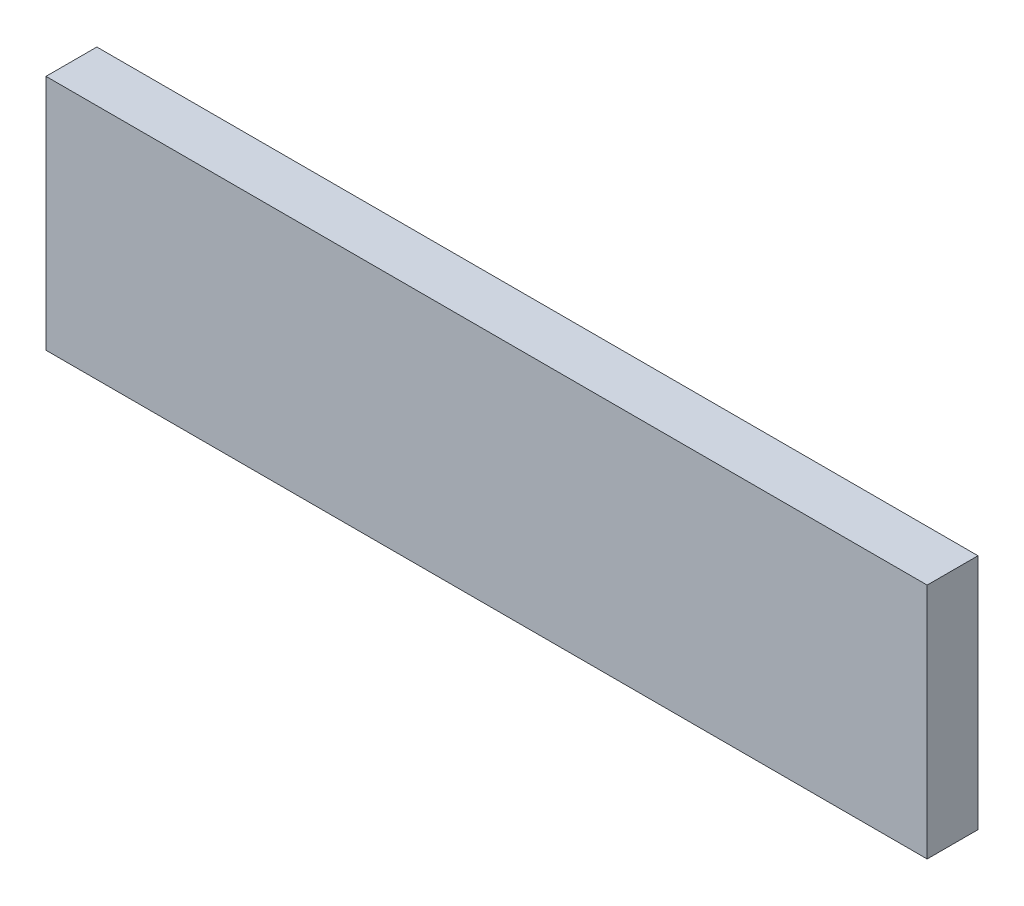
SolidWorks part; units mm, degrees
ref_plane "Front" through (0, 0, 0) normal (0, 0, 1) x (1, 0, 0)
ref_plane "Top" through (0, 0, 0) normal (0, 1, 0) x (1, 0, 0)
ref_plane "Right" through (0, 0, 0) normal (1, 0, 0) x (0, 0, -1)
sketch "Sketch1" plane through (0, 0, 0) normal (0, 0, 1) x (1, 0, 0)
  line L2 (58.3497, 188.1936) -> (58.3497, 174.1936)
  line L3 (58.3497, 174.1936) -> (110.3497, 174.1936)
  line L4 (110.3497, 188.1936) -> (110.3497, 174.1936)
  line L8 (58.3497, 188.1936) -> (110.3497, 188.1936)
  point P0 (84.3497, 180.5992)
  dimension "D1" = 52
  dimension "D2" = 14
extrude "Boss-Extrude1" add sketch "Sketch1" along normal blind 3
